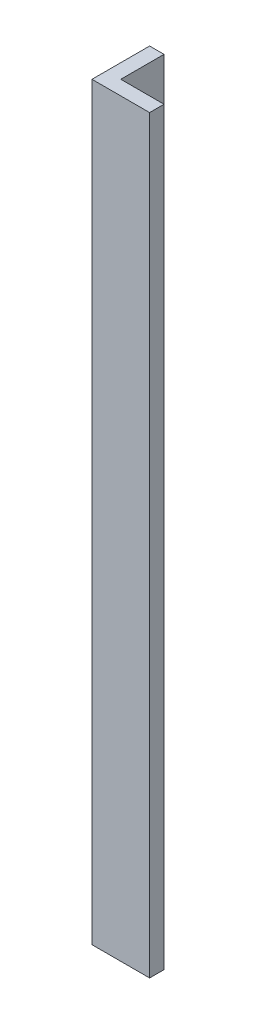
SolidWorks part; units mm, degrees
ref_plane "Front Plane" through (0, 0, 0) normal (0, 0, 1) x (1, 0, 0)
ref_plane "Top Plane" through (0, 0, 0) normal (0, 1, 0) x (1, 0, 0)
ref_plane "Right Plane" through (0, 0, 0) normal (1, 0, 0) x (0, 0, -1)
sketch "Sketch1" plane through (0, 0, 0) normal (0, 1, 0) x (1, 0, 0)
  line L1 (-16.9032, 9.3548) -> (-11.9032, 9.3548)
  line L2 (-16.9032, 9.3548) -> (-16.9032, -10.6452)
  line L3 (-16.9032, -10.6452) -> (-8.5806, -10.6452)
  line L4 (-11.9032, 9.3548) -> (-11.9032, -5.6452)
  line L5 (-11.9032, -5.6452) -> (3.0968, -5.6452)
  line L6 (-16.9032, -4.6452) -> (-16.9032, -10.6452)
  line L7 (-16.9032, -10.6452) -> (3.0968, -10.6452)
  line L8 (3.0968, -5.6452) -> (3.0968, -10.6452)
  dimension "D1" = 20
  dimension "D2" = 20
  dimension "D3" = 5
  dimension "D4" = 5
extrude "Boss-Extrude1" add sketch "Sketch1" along normal blind 260 contours L8 L5 L4 L1 L2 L3 L7
